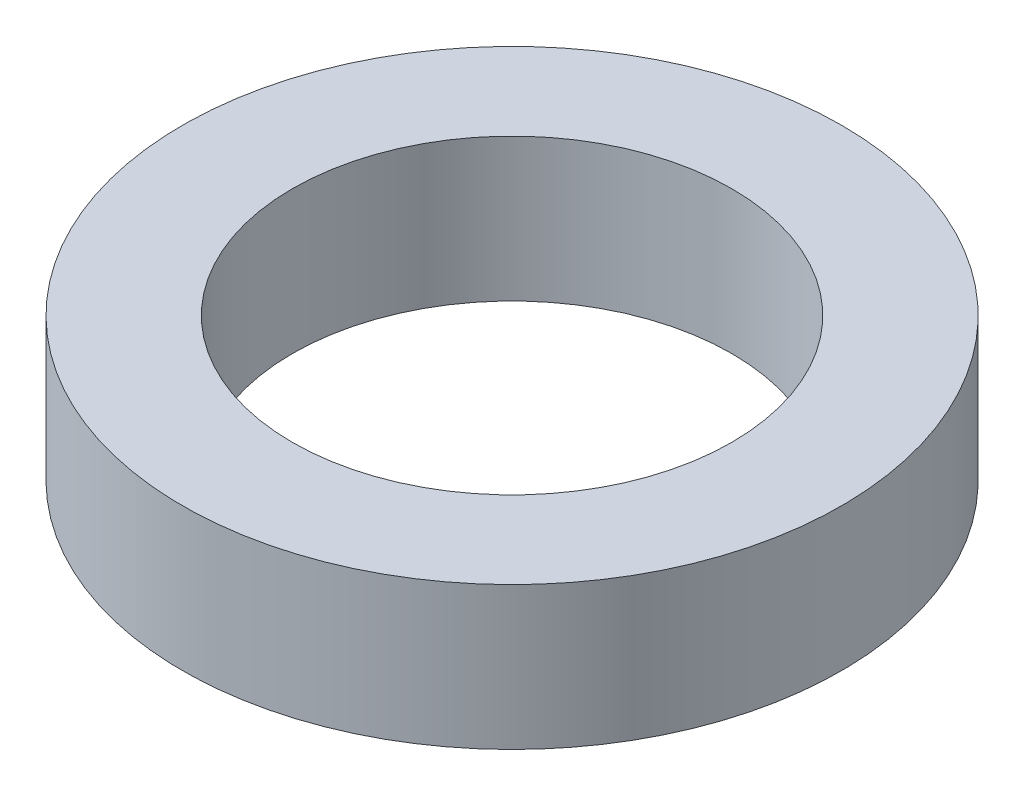
SolidWorks part; units mm, degrees
material "AISI 304"
ref_plane "前视基准面" through (0, 0, 0) normal (0, 0, 1) x (1, 0, 0)
ref_plane "上视基准面" through (0, 0, 0) normal (0, 1, 0) x (1, 0, 0)
ref_plane "右视基准面" through (0, 0, 0) normal (1, 0, 0) x (0, 0, -1)
other "Configuration Table"
sketch "草图1" plane through (0, 0, 0) normal (0, 1, 0) x (1, 0, 0)
  circle A0 centre (0, 0) radius 20
  circle A1 centre (0, 0) radius 30
  dimension "D1" = 40
  dimension "D2" = 60
extrude "凸台-拉伸1" add sketch "草图1" along normal blind 13
